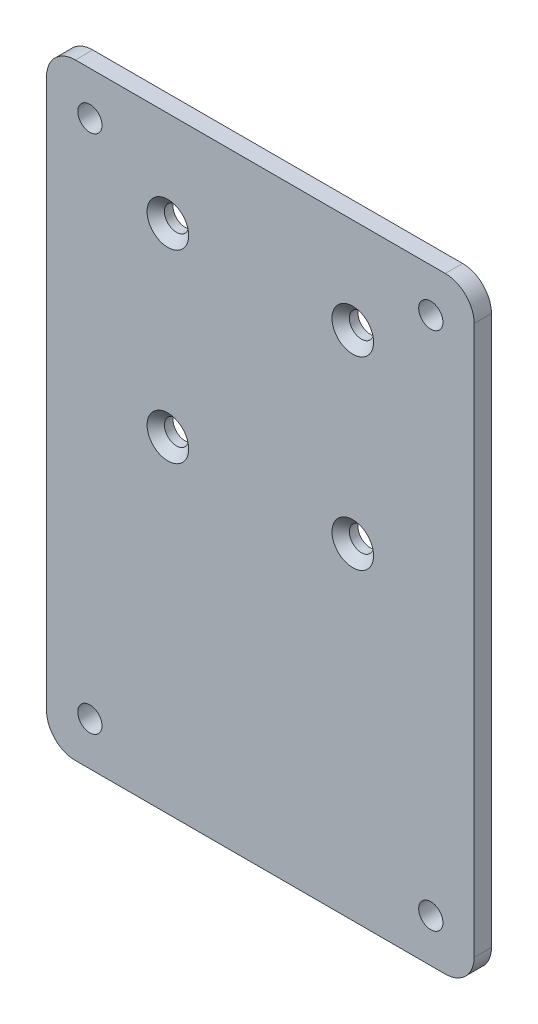
SolidWorks part; units mm, degrees
ref_plane "正面" through (0, 0, 0) normal (0, 0, 1) x (1, 0, 0)
ref_plane "平面" through (0, 0, 0) normal (0, 1, 0) x (1, 0, 0)
ref_plane "右側面" through (0, 0, 0) normal (1, 0, 0) x (0, 0, -1)
sketch "ｽｹｯﾁ1" plane through (0, 0, 0) normal (0, 0, 1) x (1, 0, 0)
  line L0 (0, 0) -> (0, 20) construction
  line L1 (-37, 52.5) -> (37, 52.5)
  line L2 (-37, 52.5) -> (-37, -52.5)
  line L3 (-37, -52.5) -> (37, -52.5)
  line L4 (37, 52.5) -> (37, -52.5)
  line L5 (-37, 52.5) -> (37, -52.5) construction
  line L6 (-37, -52.5) -> (37, 52.5) construction
  line L7 (-16, 36) -> (16, 36) construction
  line L8 (-16, 36) -> (-16, 4) construction
  line L9 (-16, 4) -> (16, 4) construction
  line L10 (16, 36) -> (16, 4) construction
  line L11 (-16, 36) -> (16, 4) construction
  line L12 (-16, 4) -> (16, 36) construction
  line L13 (-29.5, -45) -> (29.5, -45) construction
  line L14 (-29.5, -45) -> (-29.5, 45) construction
  line L15 (-29.5, 45) -> (29.5, 45) construction
  line L16 (29.5, -45) -> (29.5, 45) construction
  line L17 (-29.5, -45) -> (29.5, 45) construction
  line L18 (-29.5, 45) -> (29.5, -45) construction
  circle A0 centre (-16, 36) radius 2.1
  circle A1 centre (16, 36) radius 2.1
  circle A2 centre (-16, 4) radius 2.1
  circle A3 centre (16, 4) radius 2.1
  circle A4 centre (-29.5, 45) radius 2.1
  circle A5 centre (-29.5, -45) radius 2.1
  circle A6 centre (29.5, 45) radius 2.1
  circle A7 centre (29.5, -45) radius 2.1
  point P0 (0, 0)
  point P5 (0, 0)
  point P18 (0, 0)
  dimension "D1" = 4.2
  dimension "D4" = 7.5
  dimension "D2" = 32
  dimension "D3" = 32
  dimension "D5" = 7.5
  dimension "D6" = 59
  dimension "D7" = 90
  dimension "D8" = 20
extrude "ﾎﾞｽ - 押し出し1" add sketch "ｽｹｯﾁ1" along normal blind 3
fillet "ﾌｨﾚｯﾄ1" radius 5 4 edges at (-37, -52.5, 1.5) (37, -52.5, 1.5) (-37, 52.5, 1.5) (37, 52.5, 1.5)
chamfer "面取り1" distance 1.5 angle 45 4 edges at (18.1, 4, 3) (-13.9, 4, 3) (-13.9, 36, 3) (18.1, 36, 3)
